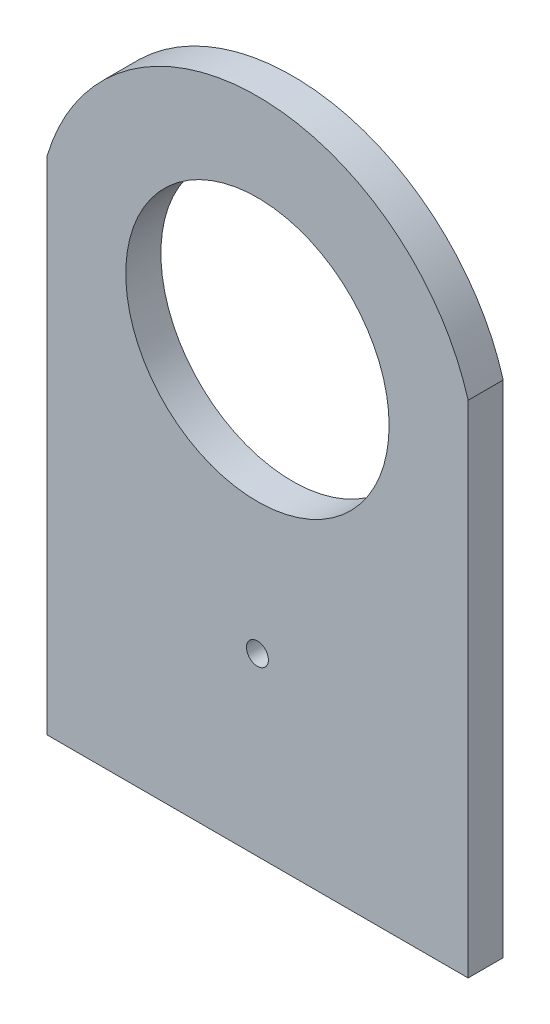
SolidWorks part; units mm, degrees
ref_plane "前视基准面" through (0, 0, 0) normal (0, 0, 1) x (1, 0, 0)
ref_plane "上视基准面" through (0, 0, 0) normal (0, 1, 0) x (1, 0, 0)
ref_plane "右视基准面" through (0, 0, 0) normal (1, 0, 0) x (0, 0, -1)
other "Configuration Table"
sketch "草图1" plane through (0, 0, 0) normal (0, 0, 1) x (1, 0, 0)
  line L0 (0, 0) -> (0, 150.9585) construction
  line L3 (-48, 114) -> (-48, 0)
  line L4 (-48, 0) -> (48, 0)
  line L5 (48, 114) -> (48, 0)
  circle A0 centre (0, 100) radius 30
  arc A2 (48, 114) -> (-48, 114) centre (0, 100) ccw
  dimension "D3" = 60
  dimension "D4" = 50
  dimension "D1" = 96
  dimension "D2" = 100
extrude "凸台-拉伸1" add sketch "草图1" along normal blind 8
sketch "草图2" plane through (0, 0, 0) normal (0, -1, 0) x (1, 0, 0)
  line L0 (-53.8408, 4) -> (58.1589, 4) construction
  line L1 (0, 20.308) -> (0, -17.9139) construction
  line L2 (-48, 8) -> (48, 8) construction
  line L3 (-48, 0) -> (48, 0) construction
  circle A0 centre (35, 4) radius 2.5
  circle A1 centre (-35, 4) radius 2.5
  dimension "D2" = 5
  dimension "D1" = 70
extrude "切除-拉伸1" cut sketch "草图2" against normal blind 50
sketch "草图3" plane through (0, 0, 8) normal (0, 0, 1) x (1, 0, 0)
  line L0 (0, 0) -> (0, 95.092) construction
  circle A0 centre (0, 40) radius 2.5
  dimension "D1" = 5
  dimension "D2" = 40
extrude "切除-拉伸2" cut sketch "草图3" against normal blind 20
